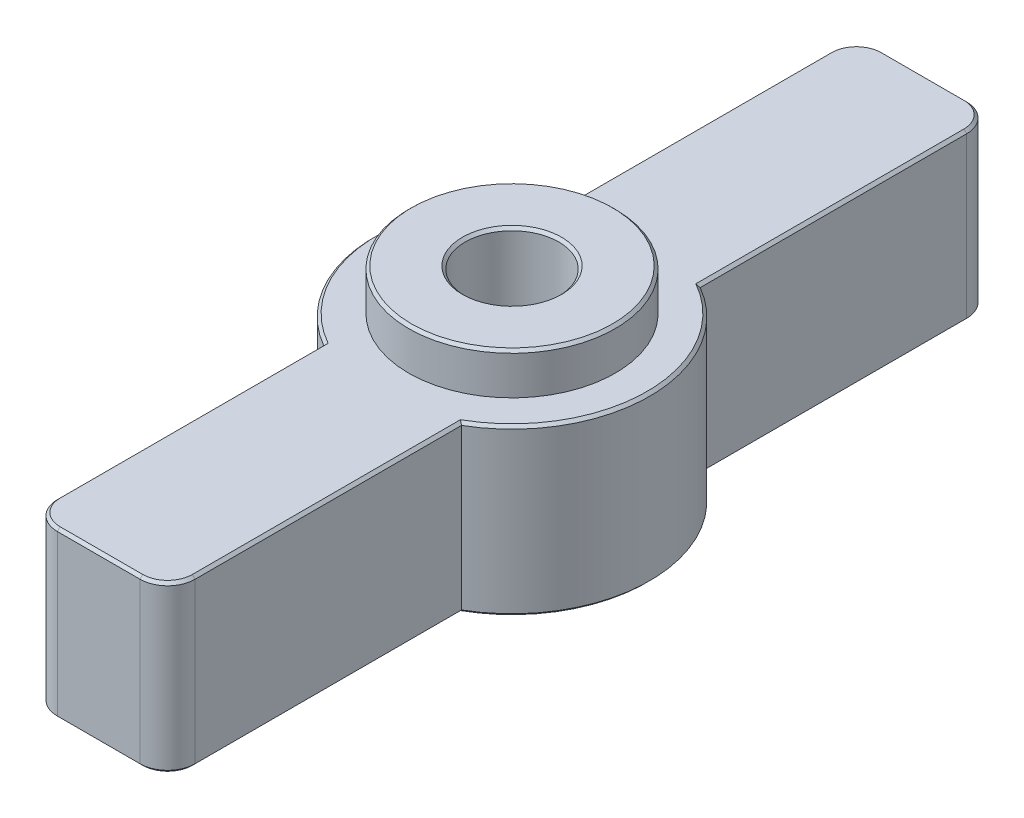
SolidWorks part; units mm, degrees
ref_plane "Front Plane" through (0, 0, 0) normal (0, 0, 1) x (1, 0, 0)
ref_plane "Top Plane" through (0, 0, 0) normal (0, 1, 0) x (1, 0, 0)
ref_plane "Right Plane" through (0, 0, 0) normal (1, 0, 0) x (0, 0, -1)
other "Configuration Table"
sketch "草图1" plane through (0, 0, 0) normal (0, 1, 0) x (1, 0, 0)
  line L0 (-5, 0) -> (5, 0) construction
  line L1 (-5, -28) -> (-5, -8.6603)
  line L2 (5, -28) -> (5, -8.6603)
  line L3 (-3, 30) -> (3, 30)
  line L4 (-3, -30) -> (3, -30)
  line L5 (-5, 8.6603) -> (-5, 28)
  line L6 (5, 8.6603) -> (5, 28)
  arc A0 (-5, 8.6603) -> (-5, -8.6603) centre (0, 0) ccw
  arc A1 (3, -30) -> (5, -28) centre (3, -28) ccw
  arc A2 (-3, -30) -> (-5, -28) centre (-3, -28) cw
  arc A3 (5, 28) -> (3, 30) centre (3, 28) ccw
  arc A4 (-5, 28) -> (-3, 30) centre (-3, 28) cw
  arc A5 (5, -8.6603) -> (5, 8.6603) centre (0, 0) ccw
  point P6 (0, 0)
  point P9 (-5, 0)
  point P12 (5, 0)
  dimension "D1" = 60
  dimension "D2" = 2
  dimension "D3" = 10
extrude "Boss-Extrude1" add sketch "草图1" along normal blind 12
sketch "草图2" plane through (0, 0, 0) normal (0, -1, 0) x (1, 0, 0)
  circle A0 centre (0, 0) radius 6.75
extrude "Cut-Extrude1" cut sketch "草图2" against normal blind 8.5
sketch "草图4" plane through (0, 12, 0) normal (0, 1, 0) x (1, 0, 0)
  circle A0 centre (0, 0) radius 7.5
  dimension "D1" = 15
extrude "Boss-Extrude2" add sketch "草图4" along normal blind 3
sketch "草图3" plane through (0, 8.5, 0) normal (0, -1, 0) x (1, 0, 0)
  circle A0 centre (0, 0) radius 3.4
  dimension "D1" = 6.8
extrude "Cut-Extrude2" cut sketch "草图3" against normal through all
chamfer "Fillet1" distance 0.2 angle 45 27 edges at (5, 12, 18.3301) (4.4142, 12, 29.4142) (0, 12, 30) (-4.4142, 12, 29.4142) (-5, 12, 18.3301) (-10, 12, 0) (0, 15, 7.5) (0, 15, -3.4) (5, 0, -18.3301) (4.4142, 0, -29.4142) (0, 0, -30) (-4.4142, 0, -29.4142) (-5, 0, -18.3301) (-5, 0, 18.3301) (-4.4142, 0, 29.4142) (0, 0, 30) (4.4142, 0, 29.4142) (5, 0, 18.3301) (-10, 0, 0) (0, 0, -6.75) (-5, 12, -18.3301) (-4.4142, 12, -29.4142) (0, 12, -30) (4.4142, 12, -29.4142) (5, 12, -18.3301) (10, 12, 0) (10, 0, 0)
